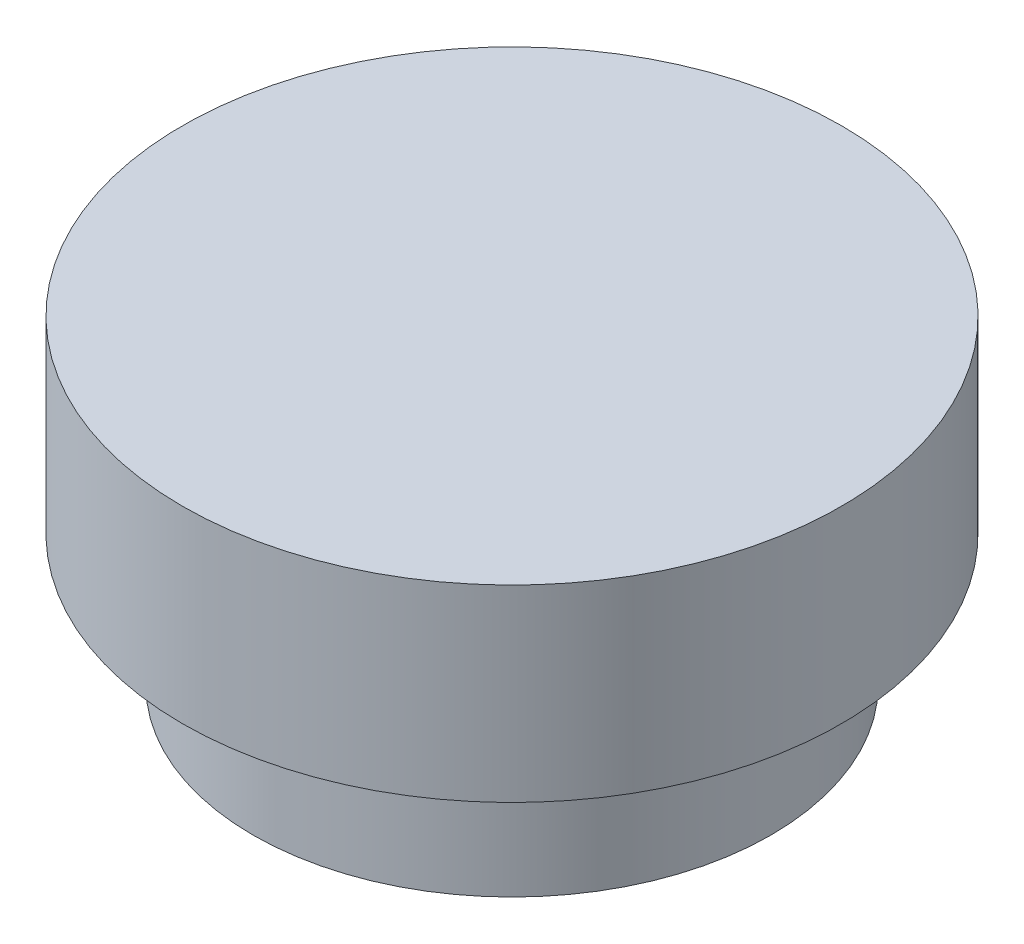
SolidWorks part; units mm, degrees
ref_plane "Front Plane" through (0, 0, 0) normal (0, 0, 1) x (1, 0, 0)
ref_plane "Top Plane" through (0, 0, 0) normal (0, 1, 0) x (1, 0, 0)
ref_plane "Right Plane" through (0, 0, 0) normal (1, 0, 0) x (0, 0, -1)
sketch "Sketch1" plane through (0, 0, 0) normal (0, 1, 0) x (1, 0, 0)
  circle A0 centre (0, 0) radius 1.25
  dimension "D1" = 2.5
extrude "Boss-Extrude1" add sketch "Sketch1" along normal blind 2.5 contours A0
sketch "Sketch2" plane through (0, 2.5, 0) normal (0, 1, 0) x (1, 0, 0)
  circle A0 centre (0, 0) radius 6.875
  dimension "D1" = 13.75
extrude "Boss-Extrude2" add sketch "Sketch2" along normal blind 3.5
sketch "Sketch3" plane through (0, 6, 0) normal (0, 1, 0) x (1, 0, 0)
  circle A0 centre (0, 0) radius 8.75
  dimension "D1" = 17.5
extrude "Boss-Extrude3" add sketch "Sketch3" along normal blind 5
